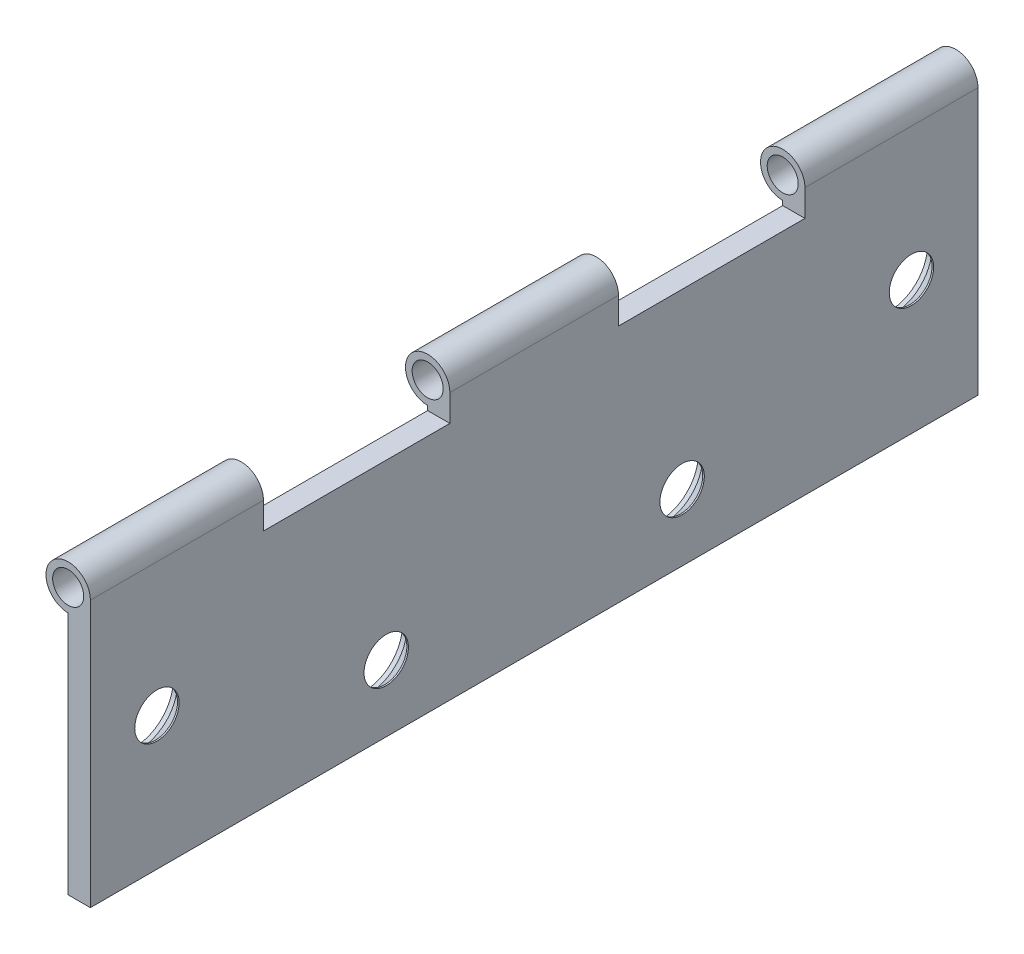
SolidWorks part; units mm, degrees
material "Chrome Stainless Steel"
ref_plane "Front Plane" through (0, 0, 0) normal (0, 0, 1) x (1, 0, 0)
ref_plane "Top Plane" through (0, 0, 0) normal (0, 1, 0) x (1, 0, 0)
ref_plane "Right Plane" through (0, 0, 0) normal (1, 0, 0) x (0, 0, -1)
sketch "Sketch1" plane through (0, 0, 0) normal (0, 0, 1) x (1, 0, 0)
  line L0 (0, 0) -> (0, 60)
  dimension "D1" = 60
extrude "Extrude-Thin1" add sketch "Sketch1" along normal mid plane 200 thin
sketch "Sketch2" plane through (0, 0, -100) normal (0, 0, -1) x (-1, 0, 0)
  circle A0 centre (0, 60) radius 5
sweep "Sweep1" add profiles "Sketch2" path edge at (0, 60, 0)
sketch "Sketch3" plane through (0, 0, -100) normal (0, 0, -1) x (-1, 0, 0)
  circle A0 centre (0, 60) radius 3.5
  arc A1 (0, 55) -> (-5, 60) centre (0, 60) ccw construction
extrude "Cut-Extrude1" cut sketch "Sketch3" against normal through all
hole_wizard "CSK for M8 Flat Head Machine Screw1" positions "Sketch5" profile "Sketch4" countersink size "M8" standard "ANSI Metric" end condition through all
sketch "Sketch5" plane through (0, 0, 0) normal (-1, 0, 0) x (0, 0, 1)
  line L0 (100, 0) -> (-100, 0) construction
  point P0 (-85, 30)
  point P2 (-33.3333, 15)
  dimension "D1" = 30
  dimension "D3" = 66.6667
  dimension "D4" = 15
  dimension "D2" = 15
sketch "Sketch4" plane through (0, 30, -85) normal (0, 1, 0) x (0, 0, 1)
  line L0 (0, 0) -> (0, 5)
  line L1 (0, 5) -> (5, 5)
  line L2 (5, 5) -> (5, 4.65)
  line L3 (5, 4.65) -> (8.65, 1)
  line L4 (8.65, 1) -> (8.65, 0)
  line L6 (8.65, 0) -> (0, 0)
  line L7 (-5, 4.65) -> (-8.65, 1) construction
  line L11 (0, -6.35) -> (0, 107.95) construction
  dimension "Thru Hole Dia." = 10
  dimension "Thru Hole Depth" = 5
  dimension "C'Sink Dia." = 17.3
  dimension "C'Sink Angle" = 90
  dimension "Head Clearance" = 1
mirror "Mirror1" about plane through (0, 0, 0) normal (0, 0, 1) of "CSK for M8 Flat Head Machine Screw1"
sketch "lay out for cuts" plane through (0, 0, 0) normal (-1, 0, 0) x (0, 0, 1)
  line L1 (-100, 65) -> (-100, 55) construction
  line L2 (-100, 54) -> (100, 54)
  line L3 (-100, 54) -> (100, 54)
  line L4 (100, 55) -> (100, 65) construction
  line L5 (-100, 65) -> (-100, 54)
  line L6 (100, 54) -> (100, 65)
  line L7 (-100, 65) -> (100, 65)
  line L8 (-60, 54) -> (-60, 65)
  line L9 (-20, 54) -> (-20, 65)
  line L10 (0, 0) -> (0, 82.4559) construction
  line L11 (20, 54) -> (20, 65)
  line L12 (60, 54) -> (60, 65)
  dimension "D2" = 40
  dimension "D3" = 40
  dimension "D1" = 1
sketch "Sketch8" plane through (0, 0, 0) normal (-1, 0, 0) x (0, 0, 1)
  line L0 (-100, 54) -> (100, 54) construction
  line L2 (-100, 65) -> (100, 65) construction
  line L4 (-61, 54) -> (-19, 54)
  line L6 (-61, 65) -> (-19, 65)
  line L7 (19, 54) -> (61, 54)
  line L10 (-61, 54) -> (-61, 65)
  line L11 (-61, 54) -> (-61, 65)
  line L13 (61, 54) -> (61, 65)
  line L14 (61, 54) -> (61, 65)
  line L16 (-19, 54) -> (-19, 65)
  line L17 (-19, 54) -> (-19, 65)
  line L18 (19, 65) -> (61, 65)
  line L19 (19, 54) -> (19, 65)
  line L20 (19, 54) -> (19, 65)
  dimension "D1" = 1
  dimension "D2" = 1
  dimension "D3" = 1
  dimension "D4" = 1
extrude "2 cuts" cut sketch "Sketch8" against normal through all and the other way through all
sketch "Sketch7" plane through (0, 0, 0) normal (-1, 0, 0) x (0, 0, 1)
  line L0 (-100, 54) -> (100, 54) construction
  line L1 (100, 54) -> (100, 65) construction
  line L2 (-100, 65) -> (100, 65) construction
  line L3 (-100, 65) -> (-100, 54) construction
  line L4 (100, 55) -> (61, 55)
  line L5 (-100, 55) -> (-100, 0)
  line L6 (-100, 0) -> (100, 0)
  line L7 (100, 0) -> (100, 55)
  line L8 (100, 55) -> (59, 55)
  line L9 (-100, 55) -> (-100, 0)
  line L10 (-100, 0) -> (100, 0)
  line L11 (100, 0) -> (100, 55)
  line L12 (-100, 54) -> (-59, 54)
  line L13 (100, 54) -> (100, 65)
  line L14 (-100, 65) -> (-59, 65)
  line L15 (-100, 65) -> (-100, 54)
  line L18 (-59, 54) -> (-59, 65)
  line L19 (-59, 54) -> (-59, 65)
  line L21 (59, 54) -> (59, 65)
  line L22 (59, 54) -> (59, 65)
  line L24 (-21, 54) -> (-21, 65)
  line L25 (-21, 54) -> (-21, 65)
  line L26 (-21, 65) -> (21, 65)
  line L27 (21, 54) -> (21, 65)
  line L28 (21, 54) -> (21, 65)
  line L29 (-59, 55) -> (134, 55)
  line L30 (21, 55) -> (-21, 55)
  line L31 (59, 65) -> (100, 65)
  line L32 (59, 54) -> (100, 54)
  line L33 (-21, 54) -> (21, 54)
  line L42 (61, 55) -> (61, 54)
  line L43 (61, 55) -> (61, 54)
  line L44 (61, 54) -> (19, 54)
  line L45 (61, 54) -> (19, 54)
  line L46 (19, 54) -> (19, 55)
  line L47 (19, 54) -> (19, 55)
  line L48 (19, 55) -> (-19, 55)
  line L49 (19, 55) -> (-19, 55)
  line L50 (-19, 55) -> (-19, 54)
  line L51 (-19, 55) -> (-19, 54)
  line L52 (-19, 54) -> (-61, 54)
  line L53 (-19, 54) -> (-61, 54)
  line L54 (-61, 54) -> (-61, 55)
  line L55 (-61, 54) -> (-61, 55)
  line L56 (-61, 55) -> (-100, 55)
  line L57 (-61, 55) -> (-100, 55)
  dimension "D1" = 0
  dimension "D2" = 1
  dimension "D3" = 1
  dimension "D4" = 1
  dimension "D5" = 1
extrude "3 cuts" [suppressed] cut sketch "Sketch7" against normal through all and the other way through all contours L14 L19 L12 L15 | L26 L28 L33 L25 | L31 L13 L32 L22
equation "\"D1@Sketch5\"= \"D1@Sketch1\" / 2"
equation "\"D3@Sketch5\"= \"D1@Extrude-Thin1\" / 3"
equation "\"D2@lay out for cuts\" = \"D1@Extrude-Thin1\" / 5"
equation "\"D3@lay out for cuts\" = \"D1@Extrude-Thin1\" / 5"
